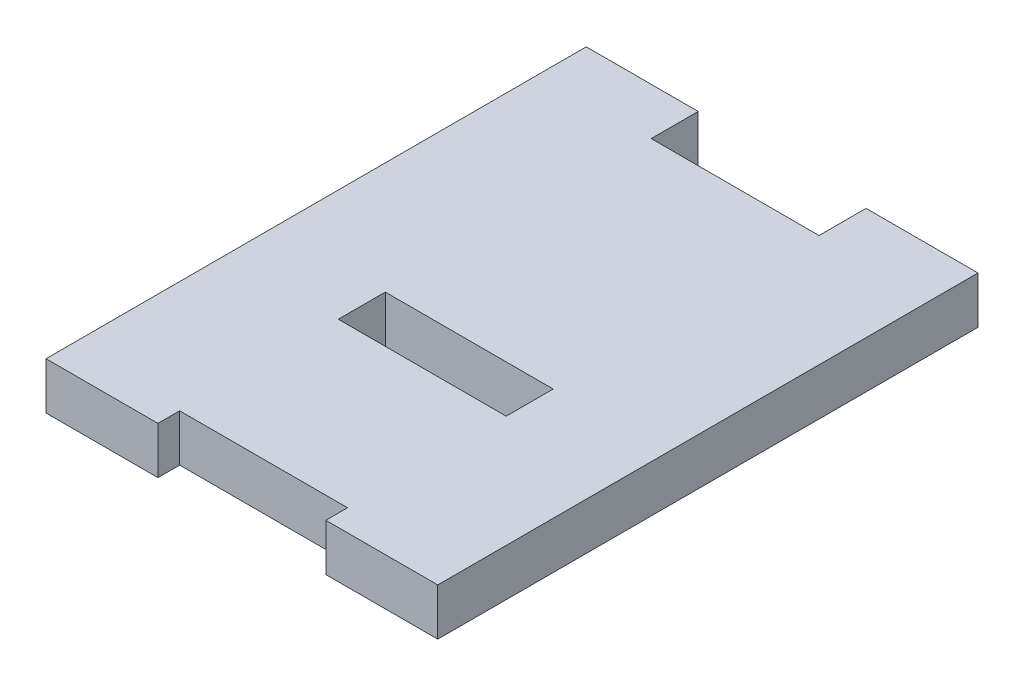
SolidWorks part; units mm, degrees
ref_plane "Front Plane" through (0, 0, 0) normal (0, 0, 1) x (1, 0, 0)
ref_plane "Top Plane" through (0, 0, 0) normal (0, 1, 0) x (1, 0, 0)
ref_plane "Right Plane" through (0, 0, 0) normal (1, 0, 0) x (0, 0, -1)
sketch "Sketch1" plane through (0, 0, 0) normal (0, 1, 0) x (1, 0, 0)
  line L1 (0, 0) -> (44.45, 0)
  line L2 (0, 0) -> (0, 61.3)
  line L3 (0, 61.3) -> (44.45, 61.3)
  line L4 (44.45, 0) -> (44.45, 61.3)
  dimension "D1" = 61.3
  dimension "D2" = 44.45
extrude "Boss-Extrude1" add sketch "Sketch1" along normal blind 5.334
sketch "Sketch2" plane through (0, 5.334, 0) normal (0, 1, 0) x (1, 0, 0)
  line L0 (0, 0) -> (44.45, 0) construction
  line L1 (12.7, 0) -> (31.75, 0)
  line L2 (12.7, 0) -> (12.7, 2.4638)
  line L3 (12.7, 2.4638) -> (31.75, 2.4638)
  line L4 (31.75, 0) -> (31.75, 2.4638)
  line L5 (44.45, 61.3) -> (0, 61.3) construction
  line L6 (12.7, 25.7978) -> (31.75, 25.7978)
  line L7 (12.7, 25.7978) -> (12.7, 20.4638)
  line L8 (12.7, 20.4638) -> (31.75, 20.4638)
  line L9 (31.75, 25.7978) -> (31.75, 20.4638)
  line L10 (12.7, 61.3) -> (31.75, 61.3)
  line L11 (12.7, 61.3) -> (12.7, 55.966)
  line L12 (12.7, 55.966) -> (31.75, 55.966)
  line L13 (31.75, 61.3) -> (31.75, 55.966)
  line L14 (12.7, 55.966) -> (12.7, 25.7978) construction
  line L15 (12.7, 20.4638) -> (12.7, 2.4638) construction
  line L16 (31.75, 2.4638) -> (31.75, 20.4638) construction
  line L17 (31.75, 25.7978) -> (31.75, 55.966) construction
  line L18 (0, 61.3) -> (0, 0) construction
  line L20 (12.7, 25.7978) -> (0, 25.7978) construction
  line L21 (31.75, 25.7978) -> (44.45, 25.7978) construction
  line L22 (44.45, 0) -> (44.45, 61.3) construction
  dimension "D1" = 19.05
  dimension "D2" = 5.334
  dimension "D3" = 2.4638
  dimension "D4" = 18
  dimension "D5" = 30.1682
extrude "Cut-Extrude1" cut sketch "Sketch2" against normal through all
equation "\"material\"= \"gmaterial@base.assembly\""
equation "\"D1@Boss-Extrude1\"=\"material\""
equation "\"D2@Sketch2\"=\"material\""
equation "\"D3@Sketch2\"=\"acrylic_sm@base.assembly\""
